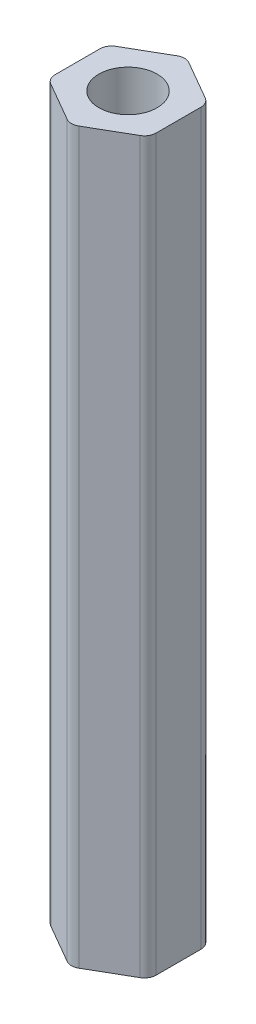
SolidWorks part; units mm, degrees
ref_plane "Front Plane" through (0, 0, 0) normal (0, 0, 1) x (1, 0, 0)
ref_plane "Top Plane" through (0, 0, 0) normal (0, 1, 0) x (1, 0, 0)
ref_plane "Right Plane" through (0, 0, 0) normal (1, 0, 0) x (0, 0, -1)
sketch "Sketch1" plane through (0, 0, 0) normal (0, 1, 0) x (1, 0, 0)
  line L1 (8.6603, -5) -> (8.6603, 5)
  line L2 (8.6603, 5) -> (0, 10)
  line L3 (0, 10) -> (-8.6603, 5)
  line L4 (-8.6603, 5) -> (-8.6603, -5)
  line L5 (-8.6603, -5) -> (0, -10)
  line L6 (0, -10) -> (8.6603, -5)
  circle A0 centre (0, 0) radius 10 construction
  circle A1 centre (0, 0) radius 5
  dimension "D1" = 20
  dimension "D2" = 10
extrude "Boss-Extrude1" add sketch "Sketch1" along normal blind 125
fillet "Fillet1" radius 2 6 edges at (-8.6603, 62.5, 5) (-8.6603, 62.5, -5) (0, 62.5, -10) (8.6603, 62.5, -5) (8.6603, 62.5, 5) (0, 62.5, 10)
